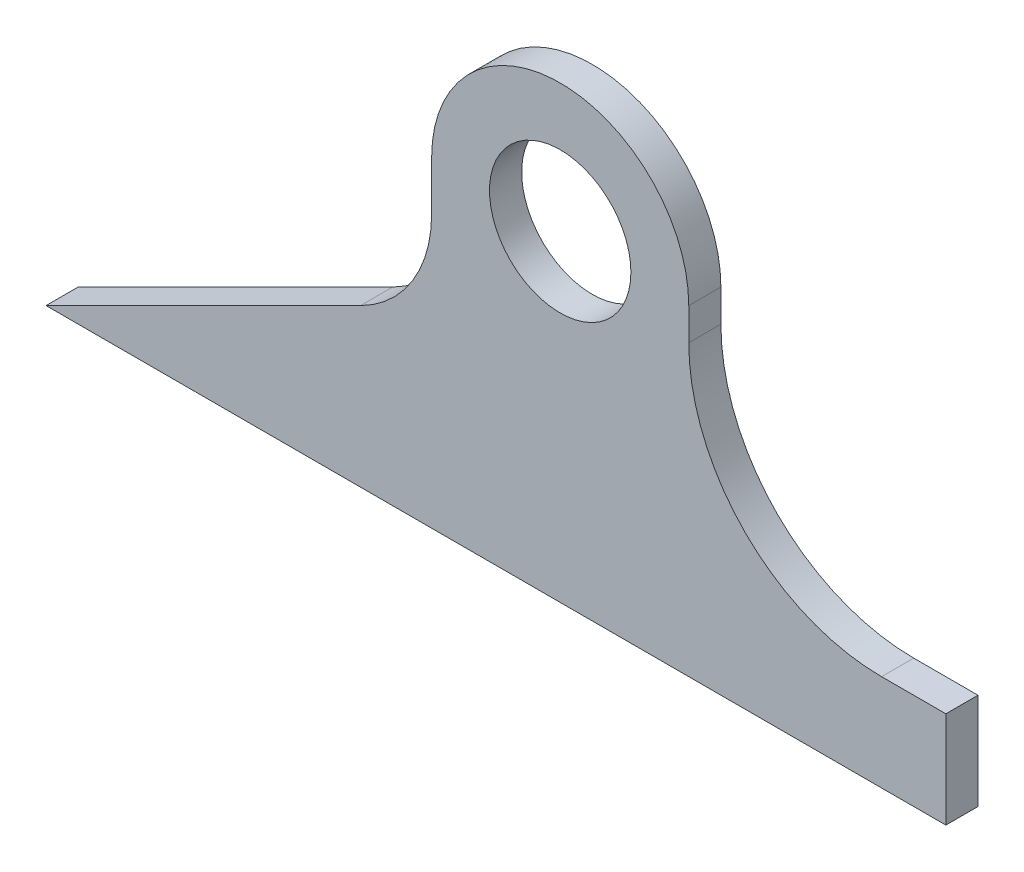
SolidWorks part; units mm, degrees
ref_plane "Front Plane" through (0, 0, 0) normal (0, 0, 1) x (1, 0, 0)
ref_plane "Top Plane" through (0, 0, 0) normal (0, 1, 0) x (1, 0, 0)
ref_plane "Right Plane" through (0, 0, 0) normal (1, 0, 0) x (0, 0, -1)
sketch "Sketch1" plane through (0, 0, 0) normal (0, 0, 1) x (1, 0, 0)
  line L5 (-40, -16.6478) -> (-100, -16.6478)
  line L10 (-40, 33.3522) -> (-40, 25.7129)
  line L11 (-40, -16.6478) -> (40, -16.6478)
  line L12 (40, -1.6478) -> (40, -16.6478)
  line L13 (40, -1.6478) -> (30, -1.6478)
  line L14 (0, 28.3522) -> (0, 33.3522)
  line L15 (-100, -16.6478) -> (-51.0557, 7.8244)
  circle A2 centre (-20, 33.3522) radius 11
  arc A5 (0, 33.3522) -> (-40, 33.3522) centre (-20, 33.3522) ccw
  arc A6 (0, 28.3522) -> (30, -1.6478) centre (30, 28.3522) ccw
  arc A7 (-51.0557, 7.8244) -> (-40, 25.7129) centre (-60, 25.7129) ccw
  point P0 (0, 0)
  point P16 (-40, 13.3522)
  dimension "D4" = 20
  dimension "D6" = 50
  dimension "D7" = 15
  dimension "D8" = 22
  dimension "D5" = 30
  dimension "D9" = 20
  dimension "D1" = 80
  dimension "D2" = 60
  dimension "D3" = 30
extrude "Boss-Extrude1" add sketch "Sketch1" along normal blind 5
